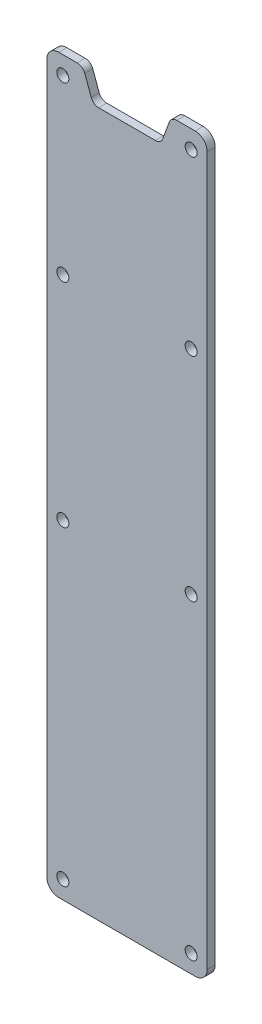
SolidWorks part; units mm, degrees
ref_plane "Alzado" through (0, 0, 0) normal (0, 0, 1) x (1, 0, 0)
ref_plane "Planta" through (0, 0, 0) normal (0, 1, 0) x (1, 0, 0)
ref_plane "Vista lateral" through (0, 0, 0) normal (1, 0, 0) x (0, 0, -1)
sketch "Croquis1" plane through (0, 0, 0) normal (0, 0, 1) x (1, 0, 0)
  line L1 (-17, 88.75) -> (17, 88.75)
  line L2 (-20, 85.75) -> (-20, -90.75)
  line L3 (-17, -93.75) -> (17, -93.75)
  line L4 (20, 85.75) -> (20, -90.75)
  circle A2 centre (-16, 84.25) radius 1.5
  circle A3 centre (16, 84.25) radius 1.5
  circle A4 centre (-16, 41.25) radius 1.5
  circle A5 centre (16, 41.25) radius 1.5
  circle A6 centre (-16, -11.75) radius 1.5
  circle A7 centre (16, -11.75) radius 1.5
  circle A8 centre (-16, -89.25) radius 1.5
  circle A9 centre (16, -89.25) radius 1.5
  arc A11 (-17, 88.75) -> (-20, 85.75) centre (-17, 85.75) ccw
  arc A12 (17, 88.75) -> (20, 85.75) centre (17, 85.75) cw
  arc A13 (17, -93.75) -> (20, -90.75) centre (17, -90.75) ccw
  arc A14 (-20, -90.75) -> (-17, -93.75) centre (-17, -90.75) ccw
  dimension "D2" = 3
  dimension "D1" = 176.5
  dimension "D3" = 43
  dimension "D4" = 53
  dimension "D5" = 4.5
  dimension "D6" = 4.5
  dimension "D7" = 4.5
  dimension "D8" = 43
  dimension "D9" = 53
  dimension "D10" = 4.5
  dimension "D11" = 32
  dimension "D12" = 32
  dimension "D13" = 40
  dimension "D15" = 32
  dimension "D16" = 4
  dimension "D17" = 4
  dimension "D18" = 4
  dimension "D19" = 4
extrude "Saliente-Extruir1" add sketch "Croquis1" along normal blind 2
sketch "Croquis2" plane through (0, 0, 2) normal (0, 0, 1) x (1, 0, 0)
  line L0 (-17, 88.75) -> (-12.4004, 88.75)
  line L1 (17, 88.75) -> (-17, 88.75) construction
  line L2 (-10.521, 87.434) -> (-8.9312, 83.066)
  line L3 (-7.0518, 81.75) -> (7.0518, 81.75)
  line L4 (8.9312, 83.066) -> (10.521, 87.434)
  line L5 (12.4004, 88.75) -> (17, 88.75)
  arc A0 (10.521, 87.434) -> (12.4004, 88.75) centre (12.4004, 86.75) cw
  arc A1 (7.0518, 81.75) -> (8.9312, 83.066) centre (7.0518, 83.75) ccw
  arc A2 (-8.9312, 83.066) -> (-7.0518, 81.75) centre (-7.0518, 83.75) ccw
  arc A3 (-12.4004, 88.75) -> (-10.521, 87.434) centre (-12.4004, 86.75) cw
  point P12 (11, 88.75)
  point P19 (-11, 88.75)
  line M7 (17, 88.75) -> (-17, 88.75)
  dimension "D6" = 2
  dimension "D1" = 6
  dimension "D2" = 6
  dimension "D3" = 7
  dimension "D4" = 110
  dimension "D5" = 110
extrude "Cortar-Extruir1" cut sketch "Croquis2" against normal blind 2 and the other way through all contours A3 L2 A2 L3 A1 L4 A0 M7
